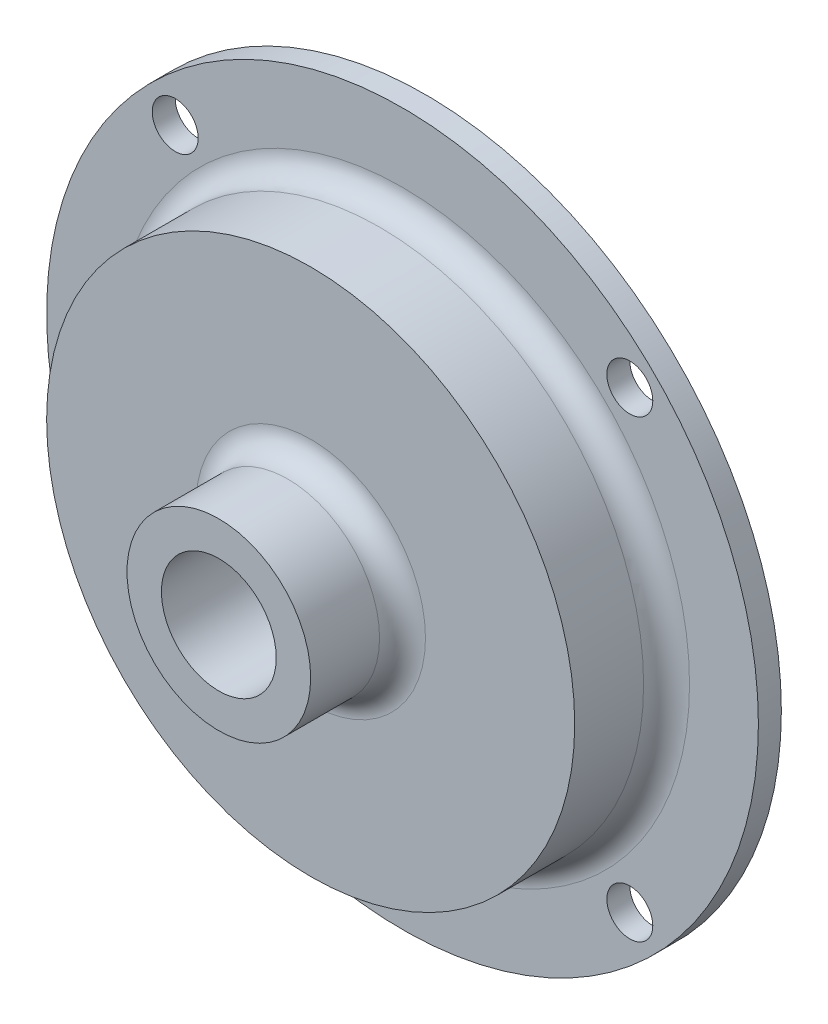
SolidWorks part; units mm, degrees
material "PW40:6:Sc:0:Re:24:"
ref_plane "Front" through (0, 0, 0) normal (0, 0, 1) x (1, 0, 0)
ref_plane "Top" through (0, 0, 0) normal (0, 1, 0) x (1, 0, 0)
ref_plane "Right" through (0, 0, 0) normal (1, 0, 0) x (0, 0, -1)
sketch "Sketch1" plane through (0, 0, 0) normal (0, 0, 1) x (1, 0, 0)
  line L0 (0, 0) -> (49.2125, 0) construction
  line L1 (0, 0) -> (34.7985, 34.7985) construction
  line L2 (0, 0) -> (-34.7985, 34.7985) construction
  circle A0 centre (0, 0) radius 49.2125
  circle A1 centre (0, 0) radius 44.45 construction
  circle A2 centre (31.4309, 31.4309) radius 3.175
  circle A4 centre (-31.4309, -31.4309) radius 3.175
  circle A6 centre (31.4309, -31.4309) radius 3.175
  circle A7 centre (-31.4309, 31.4309) radius 3.175
  dimension "D1" = 98.425
  dimension "D3" = 6.35
  dimension "D4" = 88.9
  dimension "D2" = 45
extrude "Base-Extrude" add sketch "Sketch1" along normal blind 3.175
sketch "Sketch2" plane through (0, 0, 3.175) normal (0, 0, 1) x (1, 0, 0)
  circle A0 centre (0, 0) radius 36.5125
  dimension "D1" = 73.025
extrude "Boss-Extrude1" add sketch "Sketch2" along normal blind 12.7
sketch "Sketch3" plane through (0, 0, 15.875) normal (0, 0, 1) x (1, 0, 0)
  circle A0 centre (0, 0) radius 12.7
  dimension "D1" = 25.4
extrude "Boss-Extrude2" add sketch "Sketch3" along normal blind 12.7
fillet "Fillet1" radius 3.175 2 edges at (36.5125, 0, 3.175) (12.7, 0, 15.875)
sketch "Sketch4" plane through (0, 0, 28.575) normal (0, 0, 1) x (1, 0, 0)
  circle A0 centre (0, 0) radius 7.9375
  dimension "D1" = 15.875
extrude "Cut-Extrude1" cut sketch "Sketch4" against normal through all
